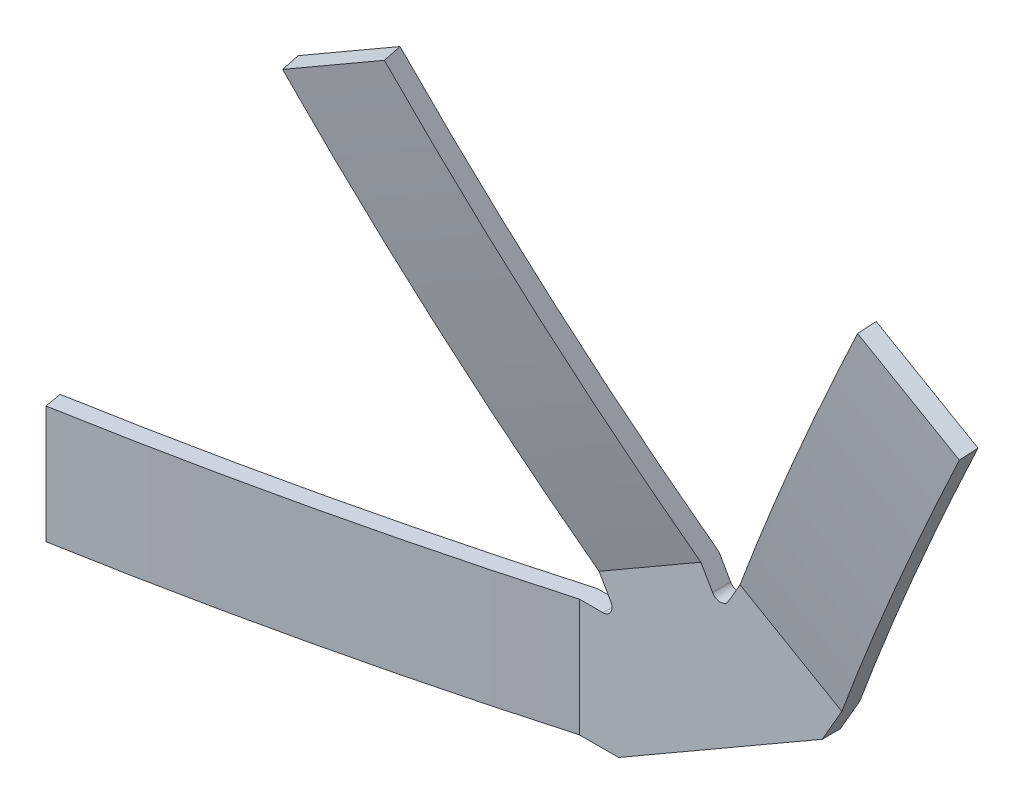
SolidWorks part; units mm, degrees
ref_plane "Ebene vorne" through (0, 0, 0) normal (0, 0, 1) x (1, 0, 0)
ref_plane "Ebene oben" through (0, 0, 0) normal (0, 1, 0) x (1, 0, 0)
ref_plane "Ebene rechts" through (0, 0, 0) normal (1, 0, 0) x (0, 0, -1)
sketch "Skizze1" plane through (0, 0, 0) normal (0, 0, 1) x (1, 0, 0)
  line L42 (29.0119, 10.25) -> (28.1458, 10.75)
  line L43 (28.1458, 10.75) -> (25.5477, 12.25)
  line L44 (25.5477, 12.25) -> (24.5477, 10.5179) construction
  line L45 (24.5477, 10.5179) -> (27.1458, 9.0179) construction
  line L46 (27.1458, 9.0179) -> (26.1147, 7.2321) construction
  line L47 (26.1147, 7.2321) -> (23.7487, 5.866) construction
  line L48 (23.7487, 5.866) -> (24.2487, 5) construction
  line L49 (24.2487, 5) -> (26.8468, 6.5)
  line L50 (26.8468, 6.5) -> (29.0119, 10.25)
  line L51 (17.7535, 16.75) -> (16.4545, 14.5)
  line L52 (14.7224, 14.5) -> (13.4234, 16.75)
  line L53 (13.4234, 16.75) -> (12.5574, 16.25)
  line L54 (12.5574, 16.25) -> (9.9593, 14.75)
  line L55 (9.9593, 14.75) -> (10.9593, 13.0179) construction
  line L56 (10.9593, 13.0179) -> (13.5574, 14.5179) construction
  line L57 (13.5574, 14.5179) -> (13.8564, 14) construction
  line L58 (17.3205, 14) -> (17.6195, 14.5179) construction
  line L59 (17.6195, 14.5179) -> (20.2176, 13.0179) construction
  line L60 (20.2176, 13.0179) -> (21.2176, 14.75) construction
  line L61 (21.2176, 14.75) -> (18.6195, 16.25)
  line L62 (18.6195, 16.25) -> (17.7535, 16.75)
  line L63 (0, 6.5) -> (0, 5.5)
  line L64 (0, 5.5) -> (0, 2.5)
  line L65 (0, 2.5) -> (2, 2.5) construction
  line L66 (2, 2.5) -> (2, 5.5) construction
  line L67 (2, 5.5) -> (2.5981, 5.5) construction
  line L68 (4.3301, 8.5) -> (4.0311, 9.0179) construction
  line L69 (4.0311, 9.0179) -> (6.6292, 10.5179) construction
  line L70 (6.6292, 10.5179) -> (5.6292, 12.25) construction
  line L71 (5.6292, 12.25) -> (3.0311, 10.75)
  line L72 (3.0311, 10.75) -> (2.1651, 10.25)
  line L73 (2.1651, 10.25) -> (3.4641, 8)
  line L74 (2.5981, 6.5) -> (0, 6.5)
  line L75 (0, -6.5) -> (4.3301, -6.5)
  line L76 (4.3301, -6.5) -> (6.9282, -5)
  line L77 (6.9282, -5) -> (6.4282, -4.134) construction
  line L78 (6.4282, -4.134) -> (4.0622, -5.5) construction
  line L79 (4.0622, -5.5) -> (2, -5.5) construction
  line L80 (2, -5.5) -> (2, -2.5) construction
  line L81 (2, -2.5) -> (0, -2.5) construction
  line L82 (0, -2.5) -> (0, -5.5)
  line L83 (0, -5.5) -> (0, -6.5)
  line L84 (24.2487, 5) -> (6.9282, -5)
  line L85 (21.2176, 14.75) -> (25.5477, 12.25)
  line L86 (9.9593, 14.75) -> (5.6292, 12.25)
  line L87 (0, 2.5) -> (0, -2.5)
  arc A4 (14.7224, 14.5) -> (16.4545, 14.5) centre (15.5885, 15) ccw
  arc A5 (13.8564, 14) -> (17.3205, 14) centre (15.5885, 15) ccw construction
  arc A6 (2.5981, 5.5) -> (4.3301, 8.5) centre (2.5981, 7.5) ccw construction
  arc A7 (2.5981, 6.5) -> (3.4641, 8) centre (2.5981, 7.5) ccw
extrude "Aufsatz-Linear austragen1" add sketch "Skizze1" along normal blind 2
sketch "Skizze3" plane through (0, 0, 2) normal (0, 0, 1) x (1, 0, 0)
  line L0 (23.3827, 13.5) -> (-24976.6173, -43287.7702) construction
  line L1 (29.0119, 10.25) -> (17.7535, 16.75) construction
  line L2 (7.7942, 13.5) -> (25007.7942, -43287.7702) construction
  line L3 (13.4234, 16.75) -> (2.1651, 10.25) construction
  line L4 (0, 0) -> (50000, 0) construction
  line L5 (0, 6.5) -> (0, -6.5) construction
  point P4 (23.3827, 13.5)
  point P9 (7.7942, 13.5)
  point P14 (0, 0)
  point P15 (23.3827, 13.5)
  point P16 (15.5885, 0)
ref_axis "DrehAchse" through (15.5885, 0, -5.4009) along (0, 0, 1)
sketch "Skizze6" plane through (0, -6.5, 0) normal (0, -1, 0) x (1, 0, 0)
  line L0 (-48.0047, 13) -> (-48.3387, 11.1052)
  line L1 (0, 2) -> (0, 0)
  arc A0 (0, 2) -> (-48.0047, 13) centre (-132.2862, -465.0574) ccw
  arc A1 (0, 0) -> (-48.3387, 11.1052) centre (-132.2862, -465.0574) ccw
  arc A2 (-0.5243, 0.1488) -> (-48.3387, 11.1052) centre (-132.2862, -465.0574) ccw construction
  dimension "D1" = 49.27
  dimension "D2" = 485.43
  dimension "D3" = 11
extrude "Aufsatz-Linear austragen5" add sketch "Skizze6" against normal blind 13
pattern_circular "Kreismuster3" count 3 over 120 about axis through (15.5885, 0, 0) along (0, 0, 1) of "Aufsatz-Linear austragen5"
